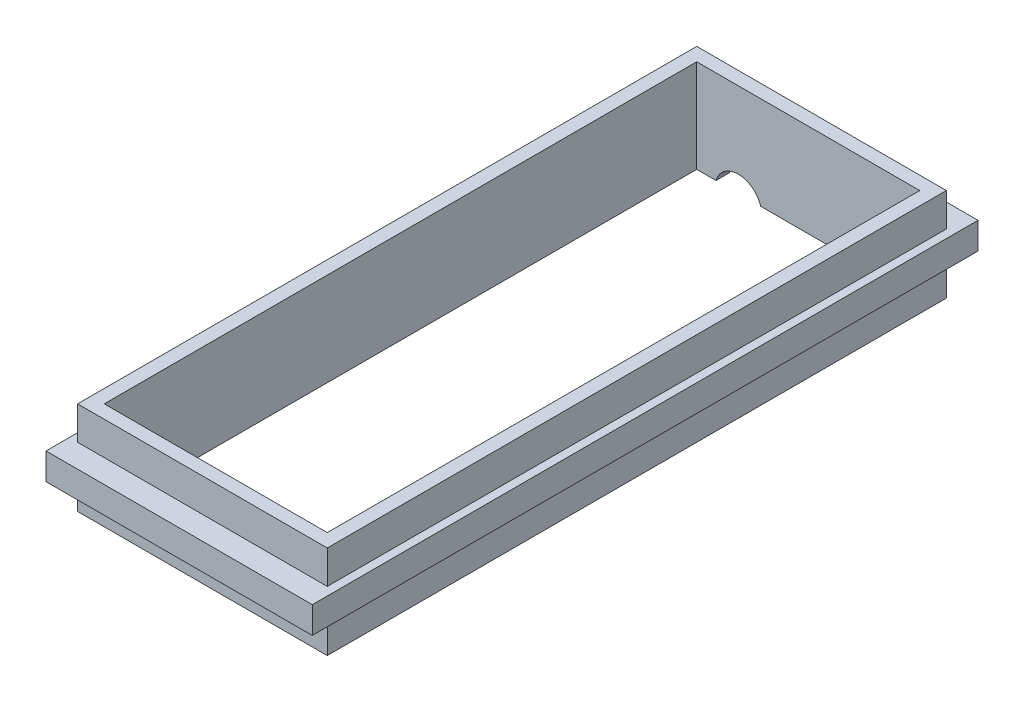
SolidWorks part; units mm, degrees
ref_plane "Front Plane" through (0, 0, 0) normal (0, 0, 1) x (1, 0, 0)
ref_plane "Top Plane" through (0, 0, 0) normal (0, 1, 0) x (1, 0, 0)
ref_plane "Right Plane" through (0, 0, 0) normal (1, 0, 0) x (0, 0, -1)
sketch "Sketch1" plane through (0, 0, 0) normal (0, 1, 0) x (1, 0, 0)
  line L0 (-16.75, 44.5) -> (16.75, 44.5)
  line L1 (-18.75, 46.5) -> (18.75, 46.5)
  line L2 (-18.75, 46.5) -> (-18.75, -46.5)
  line L3 (-18.75, -46.5) -> (18.75, -46.5)
  line L4 (18.75, 46.5) -> (18.75, -46.5)
  line L5 (0, -46.5) -> (0, 46.5) construction
  line L6 (-18.75, 0) -> (18.75, 0) construction
  line L7 (16.75, 44.5) -> (16.75, -44.5)
  line L8 (-16.75, -44.5) -> (16.75, -44.5)
  line L9 (-16.75, 44.5) -> (-16.75, -44.5)
  point P0 (0, 0)
  dimension "D1" = 93
  dimension "D2" = 37.5
  dimension "D3" = 2
extrude "Boss-Extrude1" add sketch "Sketch1" along normal blind 5
sketch "Sketch2" plane through (0, 5, 0) normal (0, 1, 0) x (1, 0, 0)
  line L1 (16.75, -44.5) -> (-16.75, -44.5)
  line L2 (16.75, -44.5) -> (16.75, 44.5)
  line L3 (16.75, 44.5) -> (-16.75, 44.5)
  line L4 (-16.75, -44.5) -> (-16.75, 44.5)
  line L5 (0, 44.5) -> (0, -44.5) construction
  line L6 (16.75, 0) -> (-16.75, 0) construction
  line L7 (20, -50) -> (-20, -50)
  line L8 (20, -50) -> (20, 50)
  line L9 (20, 50) -> (-20, 50)
  line L10 (-20, -50) -> (-20, 50)
  line L11 (0, 50) -> (0, -50) construction
  line L12 (20, 0) -> (-20, 0) construction
  point P0 (0, 0)
  point P4 (0, 0)
  dimension "D1" = 100
  dimension "D2" = 40
extrude "Boss-Extrude2" add sketch "Sketch2" along normal blind 4
sketch "Sketch3" plane through (0, 9, 0) normal (0, 1, 0) x (1, 0, 0)
  line L1 (16.75, -44.5) -> (-16.75, -44.5)
  line L2 (16.75, -44.5) -> (16.75, 44.5)
  line L3 (16.75, 44.5) -> (-16.75, 44.5)
  line L4 (-16.75, -44.5) -> (-16.75, 44.5)
  line L5 (0, 44.5) -> (0, -44.5) construction
  line L6 (16.75, 0) -> (-16.75, 0) construction
  line L7 (18.75, -46.5) -> (-18.75, -46.5)
  line L8 (18.75, -46.5) -> (18.75, 46.5)
  line L9 (18.75, 46.5) -> (-18.75, 46.5)
  line L10 (-18.75, -46.5) -> (-18.75, 46.5)
  line L11 (0, 46.5) -> (0, -46.5) construction
  line L12 (18.75, 0) -> (-18.75, 0) construction
  point P0 (0, 0)
  point P4 (0, 0)
  dimension "D1" = 93
  dimension "D2" = 37.5
extrude "Boss-Extrude3" add sketch "Sketch3" along normal blind 5
sketch "Sketch4" plane through (0, 0, -46.5) normal (0, 0, -1) x (-1, 0, 0)
  line L0 (-20, 5) -> (20, 5) construction
  line L1 (-20, 9) -> (-20, 5) construction
  circle A0 centre (-11.5, -3) radius 6
  dimension "D1" = 8
  dimension "D3" = 12
  dimension "D2" = 8.5
extrude "Cut-Extrude1" cut sketch "Sketch4" against normal blind 5
sketch "Sketch5" plane through (0, 0, -46.5) normal (0, 0, -1) x (-1, 0, 0)
  line L0 (-18.75, 5) -> (18.75, 5) construction
  line L1 (20, 9) -> (20, 5) construction
  circle A0 centre (10.5, -1) radius 3.5
  dimension "D1" = 6
  dimension "D3" = 7
  dimension "D2" = 9.5
extrude "Cut-Extrude2" cut sketch "Sketch5" against normal blind 5
